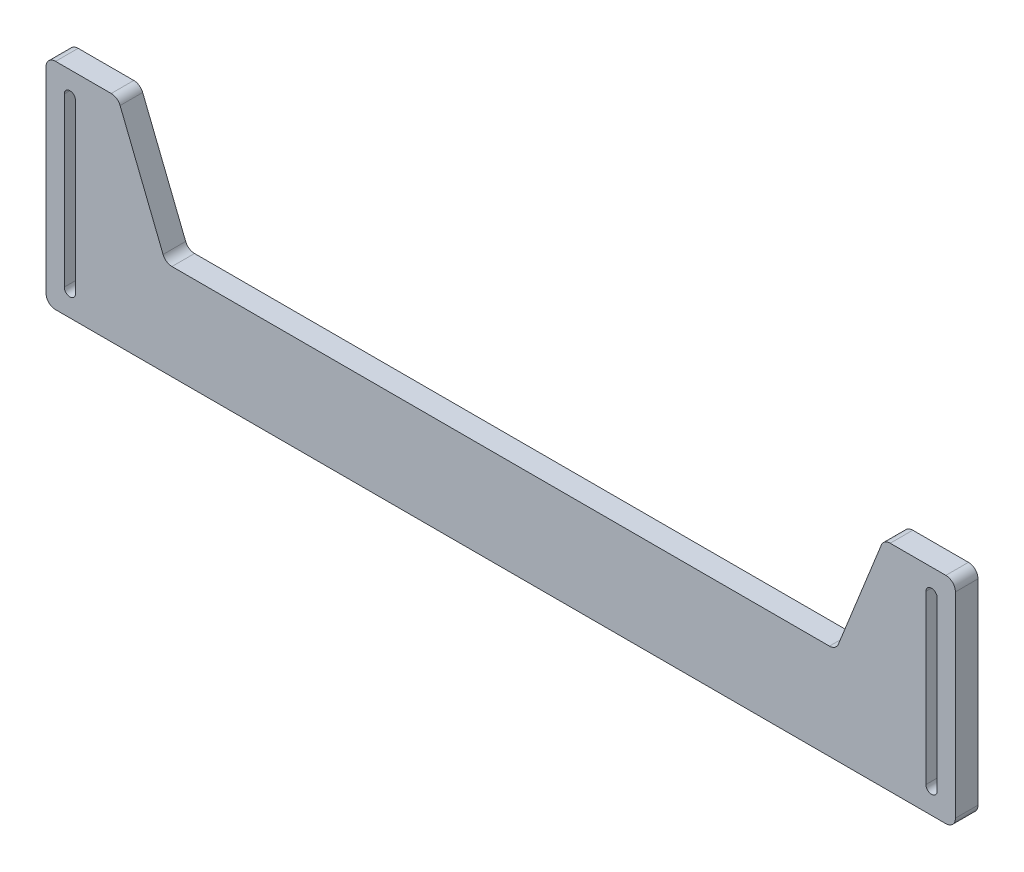
SolidWorks part; units mm, degrees
ref_plane "Front Plane" through (0, 0, 0) normal (0, 0, 1) x (1, 0, 0)
ref_plane "Top Plane" through (0, 0, 0) normal (0, 1, 0) x (1, 0, 0)
ref_plane "Right Plane" through (0, 0, 0) normal (1, 0, 0) x (0, 0, -1)
sketch "Sketch1" plane through (0, 0, 0) normal (0, 0, 1) x (1, 0, 0)
  line L0 (-120.825, -28.575) -> (-120.825, 28.575)
  line L1 (-120.825, -28.575) -> (120.825, -28.575) construction
  line L2 (-120.825, -28.575) -> (-120.825, 28.575) construction
  line L3 (-120.825, 28.575) -> (120.825, 28.575) construction
  line L4 (120.825, -28.575) -> (120.825, 28.575) construction
  line L5 (-120.825, -28.575) -> (120.825, 28.575) construction
  line L6 (-120.825, 28.575) -> (120.825, -28.575) construction
  line L7 (-120.825, 28.575) -> (-101.775, 28.575)
  line L8 (-101.775, 28.575) -> (-89.075, -3.175)
  line L9 (-89.075, -3.175) -> (89.075, -3.175)
  line L10 (0, 0) -> (0, 28.575) construction
  line L11 (120.825, -28.575) -> (120.825, 28.575)
  line L12 (120.825, 28.575) -> (101.775, 28.575)
  line L13 (101.775, 28.575) -> (89.075, -3.175)
  line L14 (-120.825, -28.575) -> (120.825, -28.575)
  line L15 (-114.475, 22.225) -> (-114.475, -22.225) construction
  line L16 (-112.975, 22.225) -> (-112.975, -22.225)
  line L17 (-115.975, 22.225) -> (-115.975, -22.225)
  line L18 (114.475, 22.225) -> (114.475, -22.225) construction
  line L19 (115.975, 22.225) -> (115.975, -22.225)
  line L20 (112.975, 22.225) -> (112.975, -22.225)
  line L21 (-114.475, 22.225) -> (114.475, 22.225) construction
  line L22 (124, -28.2989) -> (124, 28.2989) construction
  line L23 (124, -28.2989) -> (-124, -28.2989) construction
  line L24 (124, -28.2989) -> (124, 28.2989) construction
  line L25 (124, 28.2989) -> (-124, 28.2989) construction
  line L26 (-124, -28.2989) -> (-124, 28.2989) construction
  line L27 (124, -28.2989) -> (-124, 28.2989) construction
  line L28 (124, 28.2989) -> (-124, -28.2989) construction
  line L29 (-130, -28.2989) -> (-124, -28.2989) construction
  line L30 (-130, -28.2989) -> (-130, 28.2989) construction
  line L31 (-130, 28.2989) -> (-124, 28.2989) construction
  line L32 (-124, -28.2989) -> (-124, 28.2989) construction
  line L33 (-130, -28.2989) -> (-124, 28.2989) construction
  line L34 (-130, 28.2989) -> (-124, -28.2989) construction
  line L35 (130, 28.2989) -> (124, -28.2989) construction
  line L36 (130, -28.2989) -> (124, 28.2989) construction
  line L37 (130, 28.2989) -> (124, 28.2989) construction
  line L38 (130, -28.2989) -> (130, 28.2989) construction
  line L39 (130, -28.2989) -> (124, -28.2989) construction
  arc A0 (-112.975, 22.225) -> (-115.975, 22.225) centre (-114.475, 22.225) ccw
  arc A1 (-115.975, -22.225) -> (-112.975, -22.225) centre (-114.475, -22.225) ccw
  arc A2 (115.975, 22.225) -> (112.975, 22.225) centre (114.475, 22.225) ccw
  arc A3 (112.975, -22.225) -> (115.975, -22.225) centre (114.475, -22.225) ccw
  point P0 (0, 0)
  point P14 (-114.475, 0)
  point P19 (114.475, 0)
  point P28 (-127, 0)
  point P30 (0, 22.225)
  point P38 (127, 0)
  dimension "D8" = 3
  dimension "D1" = 6.35
  dimension "D2" = 6
  dimension "D3" = 19.05
  dimension "D4" = 44.45
  dimension "D5" = 25.4
  dimension "D6" = 6.35
  dimension "D7" = 6.35
  dimension "D9" = 12.7
  dimension "D10" = 9.525
  dimension "D11" = 254
extrude "Boss-Extrude1" add sketch "Sketch1" along normal mid plane 6
fillet "Fillet1" radius 2.54 8 edges at (120.825, 28.575, 0) (120.825, -28.575, 0) (-120.825, -28.575, 0) (-101.775, 28.575, 0) (-89.075, -3.175, 0) (89.075, -3.175, 0) (101.775, 28.575, 0) (-120.825, 28.575, 0)
